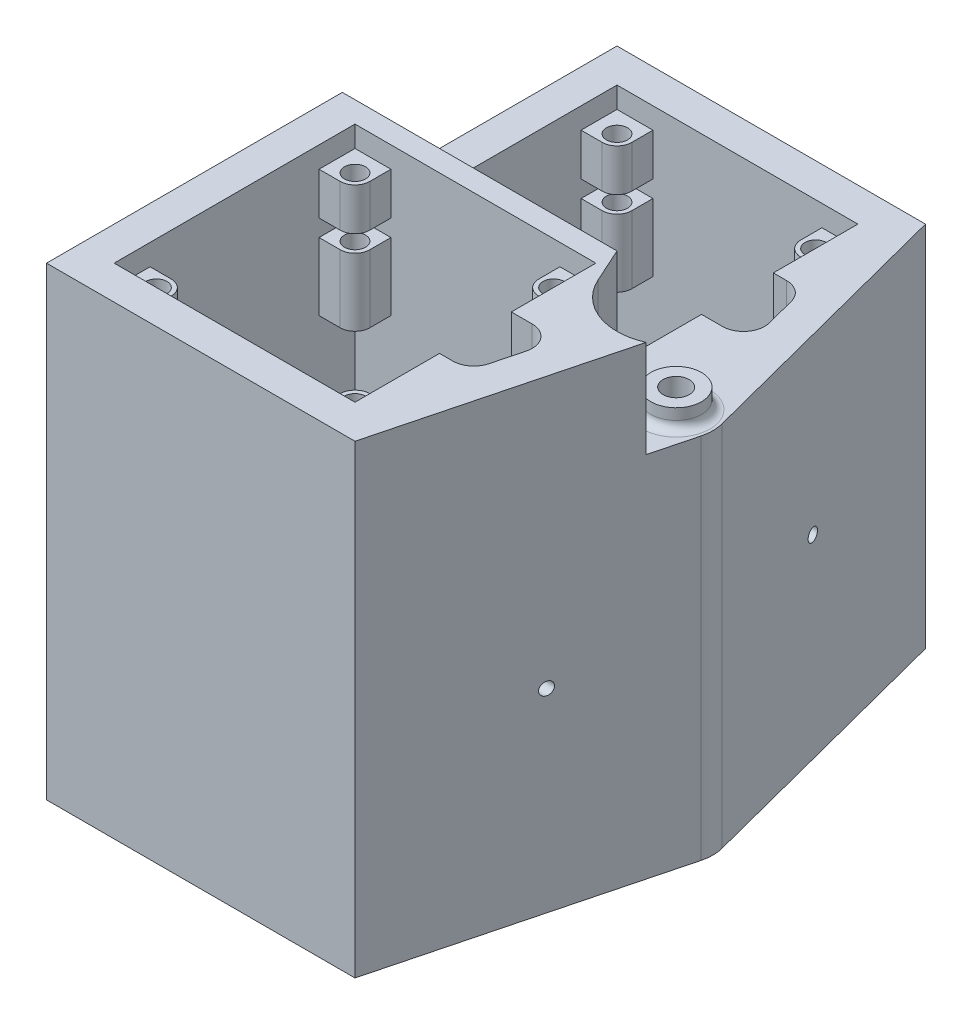
SolidWorks part; units mm, degrees
ref_plane "Alzado" through (0, 0, 0) normal (0, 0, 1) x (1, 0, 0)
ref_plane "Planta" through (0, 0, 0) normal (0, 1, 0) x (1, 0, 0)
ref_plane "Vista lateral" through (0, 0, 0) normal (1, 0, 0) x (0, 0, -1)
sketch "Croquis1" plane through (0, 0, 0) normal (0, 1, 0) x (1, 0, 0)
  line L0 (-55, 0) -> (55, 0) construction
  line L1 (-158, 67.5) -> (0, 67.5)
  line L2 (-158, 67.5) -> (-158, -67.5)
  line L3 (-158, -67.5) -> (0, -67.5)
  line L5 (-158, 67.5) -> (0, -67.5) construction
  line L6 (-158, -67.5) -> (0, 67.5) construction
  line L8 (-58.5, 0) -> (-48.5, 0) construction
  line L9 (-58.5, 0) -> (-48.5, 0) construction
  line L10 (-150, 59.5) -> (-93, 59.5) construction
  line L11 (-150, 59.5) -> (-150, 2.5) construction
  line L12 (-150, 2.5) -> (-93, 2.5) construction
  line L13 (-93, 59.5) -> (-93, 2.5) construction
  arc A0 (0, -67.5) -> (0, 67.5) centre (0, 0) ccw
  circle A1 centre (0, 0) radius 48.5 construction
  circle A2 centre (-71, 0) radius 12.5 construction
  point P4 (-79, 0)
  dimension "D1" = 135
  dimension "D2" = 97
  dimension "D3" = 25
  dimension "D4" = 10
  dimension "D5" = 8
  dimension "D6" = 57
  dimension "D7" = 8
  dimension "D8" = 158
extrude "Saliente-Extruir1" add sketch "Croquis1" along normal blind 110
sketch "Croquis2" plane through (0, 110, 0) normal (0, 1, 0) x (1, 0, 0)
  line L0 (-158, 67.5) -> (-158, -67.5) construction
  line L1 (-140, 59.5) -> (-103, 59.5)
  line L2 (-150, 49.5) -> (-150, 12.5)
  line L3 (-150, 12.5) -> (-140, 12.5)
  line L4 (-93, 49.5) -> (-93, 12.5)
  line L5 (0, 67.5) -> (-158, 67.5) construction
  line L6 (-150, 49.5) -> (-140, 49.5)
  line L7 (-140, 49.5) -> (-140, 59.5)
  line L8 (-121.5, 59.5) -> (-121.5, 2.5) construction
  line L9 (-150, 31) -> (-93, 31) construction
  line L10 (-103, 49.5) -> (-103, 59.5)
  line L11 (-93, 49.5) -> (-103, 49.5)
  line L12 (-93, 12.5) -> (-103, 12.5)
  line L13 (-103, 12.5) -> (-103, 2.5)
  line L14 (-140, 12.5) -> (-140, 2.5)
  line L16 (-140, 2.5) -> (-103, 2.5)
  point P13 (-121.5, 31)
  dimension "D1" = 8
  dimension "D2" = 8
  dimension "D3" = 37
  dimension "D4" = 37
  dimension "D5" = 57
extrude "Cortar-Extruir1" cut sketch "Croquis2" against normal blind 102
fillet "Redondeo1" [suppressed] radius 2
fillet "Redondeo2" radius 5 4 edges at (-103, 59, -12.5) (-140, 59, -12.5) (-103, 59, -49.5) (-140, 59, -49.5)
sketch "Croquis3" plane through (0, 110, 0) normal (0, 1, 0) x (1, 0, 0)
  line L0 (-150, 49.5) -> (-150, 12.5) construction
  line L1 (-150, 2.5) -> (-93, 2.5)
  line L2 (-150, 2.5) -> (-150, 59.5)
  line L3 (-150, 59.5) -> (-93, 59.5)
  line L4 (-93, 2.5) -> (-93, 59.5)
  line L5 (-140, 2.5) -> (-103, 2.5) construction
  line L6 (-103, 59.5) -> (-140, 59.5) construction
  line L7 (-93, 12.5) -> (-93, 49.5) construction
extrude "Cortar-Extruir2" cut sketch "Croquis3" against normal blind 5
sketch "Croquis4" plane through (0, 110, 0) normal (0, 1, 0) x (1, 0, 0)
  circle A0 centre (0, 0) radius 6
  dimension "D1" = 12
extrude "Cortar-Extruir3" cut sketch "Croquis4" against normal blind 100
sketch "Croquis5" plane through (0, 110, 0) normal (0, 1, 0) x (1, 0, 0)
  line L0 (-60.5, 0) -> (60.5, 0) construction
  line L1 (-89, -1000) -> (-89, 49000) construction
  line L2 (-93, 12.5) -> (-93, 49.5) construction
  circle A1 centre (-76.5, 0) radius 12.5 construction
  circle A2 centre (-76.5, 0) radius 3.1
  circle A3 centre (0, 0) radius 62 construction
  dimension "D1" = 124
  dimension "D2" = 25
  dimension "D4" = 6.2
  dimension "D3" = 4
extrude "Cortar-Extruir4" cut sketch "Croquis5" against normal blind 100
sketch "Croquis6" plane through (0, 110, 0) normal (0, 1, 0) x (1, 0, 0)
  line L0 (-68.1506, 2.5096) -> (-85, 67.5)
  line L1 (0, 67.5) -> (-158, 67.5) construction
  line L2 (-85, 67.5) -> (0, 67.5)
  line L3 (-60.5, 0) -> (60.5, 0) construction
  line L4 (-85, -67.5) -> (0, -67.5)
  line L5 (-68.1506, -2.5096) -> (-85, -67.5)
  line L6 (-93, 2.5) -> (-93, 59.5) construction
  arc A0 (0, -67.5) -> (0, 67.5) centre (0, 0) ccw
  arc A1 (0, -67.5) -> (0, 67.5) centre (0, 0) ccw construction
  arc A2 (-68.1506, 2.5096) -> (-68.1506, -2.5096) centre (-77.8306, 0) cw
  point P20 (-67.5, 0)
  dimension "D2" = 10
  dimension "D1" = 8
extrude "Cortar-Extruir5" cut sketch "Croquis6" against normal blind 32
sketch "Croquis7" plane through (0, 110, 0) normal (0, 1, 0) x (1, 0, 0)
  line L0 (-70.8172, -12.7947) -> (-85, -67.5)
  line L1 (-68.1506, -2.5096) -> (-85, -67.5) construction
  line L2 (-85, -67.5) -> (-158, -67.5)
  line L3 (-93, 2.5) -> (-158, 2.5)
  line L4 (-158, 67.5) -> (-158, -67.5) construction
  line L5 (-158, 2.5) -> (-158, -67.5)
  line L6 (-140, 2.5) -> (-103, 2.5) construction
  line L7 (-93, 2.5) -> (-89.2537, -5.7744)
  arc A0 (-89.2537, -5.7744) -> (-70.8172, -12.7947) centre (-76.5, 0) ccw
  dimension "D1" = 28
extrude "Saliente-Extruir2" add sketch "Croquis7" along normal blind 23
sketch "Croquis8" plane through (0, 133, 0) normal (0, 1, 0) x (1, 0, 0)
  line L0 (-158, 0) -> (-93, 0) construction
  line L1 (-158, 2.5) -> (-158, -67.5) construction
  line L13 (-140, 59.5) -> (-140, 54.5)
  line L14 (-145, 49.5) -> (-150, 49.5)
  line L15 (-150, 49.5) -> (-150, 12.5)
  line L16 (-150, 12.5) -> (-145, 12.5)
  line L17 (-140, 7.5) -> (-140, 2.5)
  line L18 (-140, 2.5) -> (-103, 2.5)
  line L19 (-103, 2.5) -> (-103, 7.5)
  line L20 (-98, 12.5) -> (-93, 12.5)
  line L21 (-93, 12.5) -> (-93, 49.5)
  line L22 (-93, 49.5) -> (-98, 49.5)
  line L23 (-103, 54.5) -> (-103, 59.5)
  line L24 (-103, 59.5) -> (-140, 59.5)
  line L25 (-140, 59.5) -> (-140, 54.5) construction
  line L26 (-145, 49.5) -> (-150, 49.5) construction
  line L27 (-150, 49.5) -> (-150, 12.5) construction
  line L28 (-150, 12.5) -> (-145, 12.5) construction
  line L29 (-140, 7.5) -> (-140, 2.5) construction
  line L30 (-140, 2.5) -> (-103, 2.5) construction
  line L31 (-103, 2.5) -> (-103, 7.5) construction
  line L32 (-98, 12.5) -> (-93, 12.5) construction
  line L33 (-93, 12.5) -> (-93, 49.5) construction
  line L34 (-93, 49.5) -> (-98, 49.5) construction
  line L35 (-103, 54.5) -> (-103, 59.5) construction
  line L36 (-103, 59.5) -> (-140, 59.5) construction
  line L39 (-103, -59.5) -> (-140, -59.5)
  line L40 (-103, -54.5) -> (-103, -59.5)
  line L41 (-93, -49.5) -> (-98, -49.5)
  line L42 (-93, -12.5) -> (-93, -49.5)
  line L43 (-98, -12.5) -> (-93, -12.5)
  line L44 (-103, -2.5) -> (-103, -7.5)
  line L45 (-140, -2.5) -> (-103, -2.5)
  line L46 (-140, -7.5) -> (-140, -2.5)
  line L47 (-150, -12.5) -> (-145, -12.5)
  line L48 (-150, -49.5) -> (-150, -12.5)
  line L49 (-145, -49.5) -> (-150, -49.5)
  line L50 (-140, -59.5) -> (-140, -54.5)
  arc A12 (-145, 49.5) -> (-140, 54.5) centre (-145, 54.5) ccw
  arc A13 (-103, -54.5) -> (-98, -49.5) centre (-98, -54.5) cw
  arc A14 (-98, -12.5) -> (-103, -7.5) centre (-98, -7.5) cw
  arc A15 (-140, 7.5) -> (-145, 12.5) centre (-145, 7.5) ccw
  arc A16 (-140, -7.5) -> (-145, -12.5) centre (-145, -7.5) cw
  arc A17 (-145, -49.5) -> (-140, -54.5) centre (-145, -54.5) cw
  arc A18 (-98, 12.5) -> (-103, 7.5) centre (-98, 7.5) ccw
  arc A21 (-103, 54.5) -> (-98, 49.5) centre (-98, 54.5) ccw
  arc A24 (-145, 49.5) -> (-140, 54.5) centre (-145, 54.5) ccw construction
  arc A27 (-140, 7.5) -> (-145, 12.5) centre (-145, 7.5) ccw construction
  arc A30 (-98, 12.5) -> (-103, 7.5) centre (-98, 7.5) ccw construction
  arc A33 (-103, 54.5) -> (-98, 49.5) centre (-98, 54.5) ccw construction
  dimension "D1" = 0
extrude "Cortar-Extruir6" cut sketch "Croquis8" against normal blind 102
sketch "Croquis10" plane through (0, 133, 0) normal (0, 1, 0) x (1, 0, 0)
  line L8 (-150, -12.5) -> (-150, -49.5) construction
  line L9 (-150, -59.5) -> (-93, -59.5)
  line L10 (-150, -59.5) -> (-150, -2.5)
  line L11 (-150, -2.5) -> (-93, -2.5)
  line L12 (-93, -59.5) -> (-93, -2.5)
  line L13 (-150, -59.5) -> (-93, -2.5) construction
  line L14 (-150, -2.5) -> (-93, -59.5) construction
  line L15 (-103, -2.5) -> (-140, -2.5) construction
  line L16 (-93, -49.5) -> (-93, -12.5) construction
  line L17 (-140, -59.5) -> (-103, -59.5) construction
  point P0 (-121.5, -31)
extrude "Cortar-Extruir7" cut sketch "Croquis10" against normal blind 5
sketch "Croquis11" plane through (0, 78, 0) normal (0, 1, 0) x (1, 0, 0)
  line L1 (0, 0) -> (-63, 0) construction
  circle A0 centre (0, 0) radius 63
  circle A1 centre (0, 0) radius 45 construction
  dimension "D1" = 126
  dimension "D2" = 90
extrude "Cortar-Extruir8" cut sketch "Croquis11" against normal blind 3 and the other way through all
sketch "Croquis12" plane through (0, 78, 0) normal (0, 1, 0) x (1, 0, 0)
  circle A0 centre (0, 0) radius 55
  dimension "D1" = 110
extrude "Cortar-Extruir9" cut sketch "Croquis12" against normal blind 13
sketch "Croquis13" plane through (0, 65, 0) normal (0, 1, 0) x (1, 0, 0)
  circle A0 centre (0, 0) radius 37.5 construction
  circle A1 centre (-37.5, 0) radius 1.75
  dimension "D1" = 75
  dimension "D2" = 3.5
extrude "Cortar-Extruir10" cut sketch "Croquis13" against normal blind 14
sketch "Croquis14" plane through (0, 65, 0) normal (0, 1, 0) x (1, 0, 0)
  circle A0 centre (-37.5, 0) radius 2.25
  dimension "D1" = 4.5
extrude "Cortar-Extruir11" cut sketch "Croquis14" against normal blind 5
pattern_circular "MatrizC1" count 6 over 360 about axis through (0, 0, 0) along (0, 1, 0) of "Cortar-Extruir11", "Cortar-Extruir10"
sketch "Croquis16" plane through (0, 110, 0) normal (0, 1, 0) x (1, 0, 0)
  circle A0 centre (-98, 7.5) radius 2.75 construction
  circle A1 centre (-145, 7.5) radius 2.75 construction
  circle A2 centre (-98, 54.5) radius 2.75 construction
  circle A3 centre (-145, 54.5) radius 2.75 construction
  circle A4 centre (-98, 7.5) radius 2.75 construction
  circle A5 centre (-145, 7.5) radius 2.75 construction
  circle A6 centre (-98, 54.5) radius 2.75 construction
  circle A7 centre (-145, 54.5) radius 2.75 construction
  circle A8 centre (-145, 54.5) radius 2.5
  circle A9 centre (-98, 54.5) radius 2.5
  circle A10 centre (-145, 7.5) radius 2.5
  circle A11 centre (-98, 7.5) radius 2.5
  dimension "D1" = 5
sketch "Croquis17" plane through (0, 133, 0) normal (0, 1, 0) x (1, 0, 0)
  circle A0 centre (-145, -54.5) radius 2.75 construction
  circle A1 centre (-98, -54.5) radius 2.75 construction
  circle A2 centre (-98, -7.5) radius 2.75 construction
  circle A3 centre (-145, -7.5) radius 2.75 construction
  circle A4 centre (-145, -54.5) radius 2.75 construction
  circle A5 centre (-98, -54.5) radius 2.75 construction
  circle A6 centre (-98, -7.5) radius 2.75 construction
  circle A7 centre (-145, -7.5) radius 2.75 construction
  circle A8 centre (-145, -7.5) radius 2.5
  circle A9 centre (-98, -7.5) radius 2.5
  circle A10 centre (-145, -54.5) radius 2.5
  circle A11 centre (-98, -54.5) radius 2.5
  dimension "D1" = 5
ref_plane "Plano1" through (0, 39, 0) normal (0, -1, 0) x (-1, 0, 0)
extrude "Cortar-Extruir12" cut sketch "Croquis17" against normal blind 30
sketch "Croquis18" plane through (0, 128, 0) normal (0, 1, 0) x (1, 0, 0)
  circle A4 centre (-145, -7.5) radius 2.75
  circle A5 centre (-98, -7.5) radius 2.75
  circle A6 centre (-145, -54.5) radius 2.75
  circle A7 centre (-98, -54.5) radius 2.75
  dimension "D1" = 5.5
extrude "Cortar-Extruir13" [suppressed] cut sketch "Croquis18" against normal blind 6.6
extrude "Cortar-Extruir14" cut sketch "Croquis16" against normal blind 30
sketch "Croquis19" plane through (0, 105, 0) normal (0, 1, 0) x (1, 0, 0)
  circle A4 centre (-145, 54.5) radius 2.75
  circle A5 centre (-98, 54.5) radius 2.75
  circle A6 centre (-145, 7.5) radius 2.75
  circle A7 centre (-98, 7.5) radius 2.75
  dimension "D1" = 5.5
extrude "Cortar-InsertosMotor1" [suppressed] cut sketch "Croquis19" against normal blind 6.6
sketch "Croquis20" plane through (0, 0, 0) normal (0, -1, 0) x (1, 0, 0)
  line L0 (0, -67.5) -> (-158, -67.5) construction
  line L1 (-158, 67.5) -> (0, 67.5) construction
  line L2 (0, -67.5) -> (-158, -67.5)
  line L3 (-158, 67.5) -> (0, 67.5)
  arc A0 (0, -67.5) -> (0, 67.5) centre (0, 0) ccw construction
  arc A1 (0, -67.5) -> (0, 67.5) centre (0, 0) ccw
sketch "Croquis21" plane through (-158, 0, 0) normal (1, 0, 0) x (0, 0, -1)
  line L0 (-67.5, 0) -> (67.5, 0) construction
  line L1 (-67.5, 0) -> (-81.5, 0)
  line L2 (-67.5, 0) -> (-67.5, 39)
  line L4 (-81.5, 0) -> (-81.5, 37.2595)
  line L5 (-55, 39) -> (55, 39) construction
  line L6 (-80.9119, 40.6381) -> (-67.5, 78)
  line L7 (-67.5, 78) -> (-67.5, 39)
  arc A0 (-80.9119, 40.6381) -> (-81.5, 37.2595) centre (-71.5, 37.2595) ccw
  point P12 (-81.5, 39)
  dimension "D2" = 10
  dimension "D1" = 14
sweep "Barrer1" add profiles "Croquis21" path "Croquis20"
sketch "Croquis22" plane through (0, 39, 0) normal (0, -1, 0) x (-1, 0, 0)
  line L0 (0, -74.206) -> (158, -74.206) construction
  line L1 (158, -67.5) -> (158, -80.9119) construction
  line L2 (0, 74.206) -> (158, 74.206) construction
  line L3 (158, 67.5) -> (158, 80.9119) construction
  line L4 (0, 0) -> (158, 0) construction
  line L5 (158, 2.5) -> (158, -67.5) construction
  line L6 (0, 0) -> (-52.4715, 52.4715) construction
  arc A0 (0, 74.206) -> (0, -74.206) centre (0, 0) ccw construction
  circle A1 centre (118.5, 74.206) radius 3
  circle A2 centre (39.5, 74.206) radius 3
  circle A3 centre (-52.4715, 52.4715) radius 3
  circle A4 centre (118.5, -74.206) radius 3
  circle A5 centre (39.5, -74.206) radius 3
  circle A6 centre (-52.4715, -52.4715) radius 3
  dimension "D1" = 79
  dimension "D2" = 39.5
  dimension "D3" = 6
  dimension "D4" = 45
extrude "Cortar-Extruir16" cut sketch "Croquis22" against normal through all both and the other way through all
sketch "Croquis23" plane through (0, 0, 0) normal (0, 1, 0) x (1, 0, 0)
  line L0 (0, 0) -> (-158, 0) construction
  line L1 (-158, 2.5) -> (-158, -67.5) construction
  circle A0 centre (-118.5, 74.206) radius 5
  circle A1 centre (-39.5, 74.206) radius 5
  circle A2 centre (52.4715, 52.4715) radius 5
  circle A3 centre (52.4715, 52.4715) radius 3 construction
  circle A4 centre (52.4715, -52.4715) radius 5
  circle A5 centre (-39.5, -74.206) radius 5
  circle A6 centre (-118.5, -74.206) radius 5
  dimension "D1" = 10
extrude "Cortar-Extruir17" cut sketch "Croquis23" along normal through all from offset 30
sketch "Croquis24" plane through (0, 78, 0) normal (0, 1, 0) x (1, 0, 0)
  line L0 (0, 67.5) -> (0, 96.2987)
  line L1 (0, -60.5) -> (0, 60.5) construction
  line L2 (0, -67.5) -> (0, -96.2987)
  arc A0 (0, 67.5) -> (0, -67.5) centre (0, 0) ccw
  arc A1 (0, -96.2987) -> (0, 96.2987) centre (0, 0) ccw
  arc A2 (0, -67.5) -> (0, 67.5) centre (0, 0) ccw construction
extrude "Cortar-Extruir18" cut sketch "Croquis24" against normal through all
sketch "Croquis25" plane through (-158, 0, 0) normal (-1, 0, 0) x (0, 0, 1)
  line L0 (-2.5, 133) -> (-2.5, 110) construction
  line L1 (12.5, 8) -> (52.5, 8)
  line L2 (12.5, 8) -> (12.5, 23)
  line L3 (12.5, 23) -> (52.5, 23)
  line L4 (52.5, 8) -> (52.5, 23)
  line L5 (12.5, 8) -> (52.5, 23) construction
  line L6 (12.5, 23) -> (52.5, 8) construction
  line L7 (-81.5, 0) -> (81.5, 0) construction
  line L9 (67.5, 0) -> (67.5, 78) construction
  line L10 (12.5, 31) -> (49.5, 31) construction
  point P0 (32.5, 15.5)
  dimension "D1" = 15
  dimension "D2" = 8
  dimension "D3" = 8
  dimension "D4" = 15
extrude "Cortar-Extruir19" cut sketch "Croquis25" against normal through all
ref_plane "Plano2" through (0, 42, 0) normal (0, 1, 0) x (1, 0, 0)
ref_plane "Plano4" through (0, 60, 0) normal (0, 1, 0) x (1, 0, 0)
sketch "Croquis26" plane through (0, 60, 0) normal (0, 1, 0) x (1, 0, 0)
  line L0 (-85, -67.5) -> (0, -67.5) construction
  line L1 (0, 67.5) -> (-85, 67.5) construction
  line L2 (-85, 67.5) -> (-68.1506, 2.5096) construction
  line L3 (-68.1506, -2.5096) -> (-70.8172, -12.7947) construction
  line L4 (-85, -67.5) -> (-70.8172, -12.7947) construction
  line L5 (-85, -67.5) -> (0, -67.5)
  line L6 (0, 67.5) -> (-85, 67.5)
  line L7 (-85, 67.5) -> (-68.1506, 2.5096)
  line L8 (-68.1506, -2.5096) -> (-70.8172, -12.7947)
  line L9 (-85, -67.5) -> (-70.8172, -12.7947)
  line L10 (0, 67.5) -> (0, -67.5)
  arc A0 (-68.1506, -2.5096) -> (-68.1506, 2.5096) centre (-77.8306, 0) ccw construction
  arc A1 (-68.1506, -2.5096) -> (-68.1506, 2.5096) centre (-77.8306, 0) ccw
extrude "Cortar-Extruir20" cut sketch "Croquis26" against normal through all
sketch "Croquis27" plane through (0, 133, 0) normal (0, 1, 0) x (1, 0, 0)
  line L1 (-93, -39.5) -> (-89.8742, -39.5)
  line L2 (-92.744, -65.4923) -> (-78.5611, -10.787)
  line L3 (-85.0343, -35.7548) -> (-83.2194, -28.7548)
  line L5 (-93, -22.5) -> (-88.0594, -22.5)
  line L8 (-93, -22.5) -> (-93, -39.5)
  line L9 (-158, 0) -> (-76.5, 0) construction
  line L10 (-158, 2.5) -> (-158, -67.5) construction
  line L11 (-93, 22.5) -> (-93, 39.5)
  line L12 (-93, 22.5) -> (-88.0594, 22.5)
  line L13 (-85.0343, 35.7548) -> (-83.2194, 28.7548)
  line L14 (-93, 39.5) -> (-89.8742, 39.5)
  line L15 (-150, -59.5) -> (-93, -59.5) construction
  line L16 (-93, -2.5) -> (-150, -2.5) construction
  line L17 (-93, -59.5) -> (-93, -2.5) construction
  arc A0 (-85.0343, -35.7548) -> (-89.8742, -39.5) centre (-89.8742, -34.5) cw
  arc A1 (-83.2194, -28.7548) -> (-88.0594, -22.5) centre (-88.0594, -27.5) ccw
  arc A2 (-83.2194, 28.7548) -> (-88.0594, 22.5) centre (-88.0594, 27.5) cw
  arc A3 (-85.0343, 35.7548) -> (-89.8742, 39.5) centre (-89.8742, 34.5) ccw
  dimension "D4" = 5
  dimension "D2" = 20
  dimension "D3" = 20
  dimension "D1" = 8
extrude "Cortar-Extruir21" cut sketch "Croquis27" against normal up to surface (125 mm away) up to face at (-121.5, 8, -31)
sketch "Croquis28" plane through (0, 8, 0) normal (0, 1, 0) x (1, 0, 0)
  line L0 (-83.2194, 28.7548) -> (-76.4151, 2.5096)
  line L1 (-83.2194, 28.7548) -> (-85.0343, 35.7548) construction
  line L2 (-83.2194, -28.7548) -> (-76.4151, -2.5096)
  line L3 (-85.0343, -35.7548) -> (-83.2194, -28.7548) construction
  line L4 (-93, -39.5) -> (-89.8742, -39.5) construction
  line L5 (-89.8742, 39.5) -> (-93, 39.5) construction
  line L6 (-93, -39.5) -> (-89.8742, -39.5)
  line L7 (-85.0343, -35.7548) -> (-83.2194, -28.7548)
  line L8 (-89.8742, 39.5) -> (-93, 39.5)
  line L9 (-83.2194, 28.7548) -> (-85.0343, 35.7548)
  line L10 (-93, 39.5) -> (-93, -39.5)
  arc A4 (-89.8742, -39.5) -> (-85.0343, -35.7548) centre (-89.8742, -34.5) ccw construction
  arc A5 (-85.0343, 35.7548) -> (-89.8742, 39.5) centre (-89.8742, 34.5) ccw construction
  arc A6 (-89.8742, -39.5) -> (-85.0343, -35.7548) centre (-89.8742, -34.5) ccw
  arc A7 (-85.0343, 35.7548) -> (-89.8742, 39.5) centre (-89.8742, 34.5) ccw
  arc A8 (-76.4151, -2.5096) -> (-76.4151, 2.5096) centre (-86.0951, 0) ccw
  dimension "D1" = 10
extrude "Cortar-Extruir22" cut sketch "Croquis28" along normal up to surface (15 mm away) up to face at (-88.3355, 23, 31.3582)
ref_plane "Plano3" through (0, 0, 0) normal (0, 0, -1) x (-1, 0, 0)
sketch "Croquis29" plane through (-158, 0, 0) normal (-1, 0, 0) x (0, 0, 1)
  line L0 (12.5, 8) -> (52.5, 8) construction
  line L1 (52.5, 8) -> (52.5, 23) construction
  line L2 (12.5, 23) -> (52.5, 23) construction
  line L3 (12.5, 8) -> (12.5, 23) construction
  line L4 (12.5, 8) -> (52.5, 8) construction
  line L5 (52.5, 8) -> (52.5, 23) construction
  line L6 (12.5, 23) -> (52.5, 23) construction
  line L7 (12.5, 8) -> (12.5, 23) construction
  line L8 (0, 133) -> (0, 0) construction
  line L9 (0, 35.75) -> (0, -35.75) construction
  line L10 (-2.5, 133) -> (67.5, 133) construction
  line L11 (-12.5, 8) -> (-12.5, 23)
  line L12 (-12.5, 23) -> (-52.5, 23)
  line L13 (-52.5, 8) -> (-52.5, 23)
  line L14 (-12.5, 8) -> (-52.5, 8)
extrude "Cortar-Extruir24" cut sketch "Croquis29" along normal up to surface (21.8889 mm away) from surface
sketch "Croquis30" plane through (0, 31, 0) normal (0, 1, 0) x (1, 0, 0)
  line L0 (-93, -12.5) -> (-158, -12.5) construction
  line L1 (-132, -52.5) -> (-111, -52.5)
  line L2 (-140, -44.5) -> (-140, -20.5)
  line L3 (-132, -12.5) -> (-111, -12.5)
  line L4 (-103, -44.5) -> (-103, -20.5)
  line L5 (-140, -52.5) -> (-103, -12.5) construction
  line L6 (-140, -12.5) -> (-103, -52.5) construction
  line L7 (-81.1111, -52.5) -> (-158, -52.5) construction
  line L10 (-140, -2.5) -> (-140, -7.5) construction
  line L11 (-103, -7.5) -> (-103, -2.5) construction
  arc A0 (-111, -12.5) -> (-103, -20.5) centre (-111, -20.5) cw
  arc A1 (-103, -44.5) -> (-111, -52.5) centre (-111, -44.5) cw
  arc A2 (-132, -52.5) -> (-140, -44.5) centre (-132, -44.5) cw
  arc A3 (-140, -20.5) -> (-132, -12.5) centre (-132, -20.5) cw
  point P0 (-121.5, -32.5)
  dimension "D1" = 8
extrude "Cortar-Extruir25" cut sketch "Croquis30" against normal up to next
sketch "Croquis31" plane through (-158, 0, 0) normal (-1, 0, 0) x (0, 0, 1)
  line L2 (60.5, 8) -> (60.5, 23)
  line L3 (60.5, 8) -> (60.5, 23)
  line L4 (4.5, 23) -> (60.5, 23)
  line L6 (4.5, 23) -> (4.5, 8)
  line L7 (4.5, 23) -> (4.5, 8)
  line L8 (4.5, 8) -> (60.5, 8)
  dimension "D1" = 8
  dimension "D2" = 8
extrude "Cortar-Extruir26" cut sketch "Croquis31" against normal blind 3
sketch "Croquis32" plane through (-155, 0, 0) normal (-1, 0, 0) x (0, 0, 1)
  line L0 (32.5, 23) -> (32.5, 8) construction
  line L1 (60.5, 23) -> (4.5, 23) construction
  line L2 (4.5, 8) -> (60.5, 8) construction
  line L3 (4.5, 15.5) -> (60.5, 15.5) construction
  line L4 (4.5, 23) -> (4.5, 8) construction
  line L5 (60.5, 8) -> (60.5, 23) construction
  line L6 (4.5, 23) -> (4.5, 8) construction
  circle A0 centre (8.5, 15.5) radius 1.5
  circle A1 centre (56.5, 15.5) radius 1.5
  dimension "D1" = 3
  dimension "D2" = 4
extrude "Cortar-Extruir27" cut sketch "Croquis32" against normal blind 10
sketch "Croquis33" plane through (0, 78, 0) normal (0, 1, 0) x (1, 0, 0)
  line L0 (-76.5, 0) -> (0, 0) construction
  line L1 (-55.1033, 0) -> (-72.6033, 67.5) construction
  line L2 (0, 67.5) -> (-85, 67.5) construction
  line L3 (-85, 67.5) -> (-68.1506, 2.5096) construction
  circle A0 centre (-70.0107, 57.5) radius 2.5
  circle A1 centre (-65.344, 39.5) radius 2.5
  circle A2 centre (-65.344, -39.5) radius 2.5
  circle A3 centre (-70.0107, -57.5) radius 2.5
  dimension "D2" = 10
  dimension "D3" = 5
  dimension "D4" = 18
  dimension "D1" = 12
extrude "Cortar-Extruir28" cut sketch "Croquis33" against normal through all
sketch "Croquis34" plane through (0, 78, 0) normal (0, 1, 0) x (1, 0, 0)
  circle A0 centre (-70.0107, 57.5) radius 4.25
  circle A1 centre (-65.344, 39.5) radius 4.25
  circle A2 centre (-65.344, -39.5) radius 4.25
  circle A3 centre (-70.0107, -57.5) radius 4.25
  dimension "D1" = 8.5
extrude "Cortar-Extruir29" cut sketch "Croquis34" against normal blind 5
sketch "Croquis35" plane through (0, 0, -81.5) normal (0, 0, -1) x (-1, 0, 0)
  line L0 (0, 60.5) -> (0, -60.5) construction
  line L1 (74.25, 0) -> (-74.25, 0) construction
  circle A0 centre (12, 28) radius 2.5
  circle A1 centre (12, 10) radius 2.5
  dimension "D1" = 12
  dimension "D2" = 10
  dimension "D3" = 5
  dimension "D4" = 18
extrude "Cortar-Extruir30" cut sketch "Croquis35" against normal up to next
sketch "Croquis36" plane through (0, 0, -81.5) normal (0, 0, -1) x (-1, 0, 0)
  circle A0 centre (12, 28) radius 4.25
  circle A1 centre (12, 10) radius 4.25
  dimension "D1" = 8.5
extrude "Cortar-Extruir31" cut sketch "Croquis36" against normal blind 5
mirror "Simetría2" about plane through (0, 0, 0) normal (0, 0, -1) of "Cortar-Extruir30", "Cortar-Extruir31"
sketch "Croquis37" plane through (-155, 0, 0) normal (-1, 0, 0) x (0, 0, 1)
  circle A0 centre (8.5, 15.5) radius 1.75
  circle A1 centre (56.5, 15.5) radius 1.75
  dimension "D1" = 3.5
extrude "Cortar-Extruir32" [suppressed] cut sketch "Croquis37" against normal blind 6
sketch "Croquis38" plane through (0, 110, 0) normal (0, 1, 0) x (1, 0, 0)
  circle A0 centre (-76.5, 0) radius 3.1 construction
  circle A1 centre (-76.5, 0) radius 3.1
  circle A2 centre (-76.5, 0) radius 6
  dimension "D1" = 12
extrude "Saliente-Extruir3" add sketch "Croquis38" along normal blind 4.6
fillet "Redondeo3" radius 2 1 edges at (-76.5, 110, 6)
sketch "Croquis39" plane through (-155, 0, 0) normal (-1, 0, 0) x (0, 0, 1)
  line L0 (32.5, 23) -> (32.5, 8) construction
  line L1 (4.6029, 15.5) -> (6.5514, 12.125)
  line L2 (6.5514, 12.125) -> (12.5, 12.125)
  line L5 (12.5, 18.875) -> (6.5514, 18.875)
  line L6 (6.5514, 18.875) -> (4.6029, 15.5)
  line L13 (60.5, 23) -> (4.5, 23) construction
  line L14 (4.5, 8) -> (60.5, 8) construction
  line L15 (12.5, 8) -> (12.5, 23) construction
  line L16 (12.5, 18.875) -> (12.5, 12.125)
  line L17 (11.4228, 13.8125) -> (13.0579, 16.6445) [skipped]
  line L18 (11.4228, 17.1875) -> (9.7878, 20.0195) [skipped]
  line L19 (52.5, 18.875) -> (52.5, 12.125)
  line L20 (58.4486, 18.875) -> (60.3971, 15.5)
  line L21 (52.5, 18.875) -> (58.4486, 18.875)
  line L22 (58.4486, 12.125) -> (52.5, 12.125)
  line L23 (60.3971, 15.5) -> (58.4486, 12.125)
  circle A0 centre (8.5, 15.5) radius 3.375 construction
  circle A1 centre (56.5, 15.5) radius 3.375 construction
  dimension "D1" = 6.75
extrude "Cortar-Extruir33" cut sketch "Croquis39" against normal blind 2.2 from offset 4 offset against normal yes
sketch "Croquis40" plane through (0, 105, 0) normal (0, 1, 0) x (1, 0, 0)
  line L2 (-150, 31) -> (-83.8015, 31) construction
  line L3 (-150, 59.5) -> (-150, 2.5) construction
  line L4 (-141.5, 59.5) -> (-141.5, 54.5)
  line L5 (-145, 51) -> (-150, 51)
  line L6 (-141.5, 59.5) -> (-141.5, 54.5)
  line L7 (-145, 51) -> (-150, 51)
  line L8 (-83.2194, 28.7548) -> (-85.0343, 35.7548) construction
  line L9 (-121.5, 59.5) -> (-121.5, 2.5) construction
  line L10 (-93, 59.5) -> (-150, 59.5) construction
  line L11 (-93, 2.5) -> (-158, 2.5) construction
  line L12 (-141.5, 2.5) -> (-141.5, 7.5)
  line L13 (-145, 11) -> (-150, 11)
  line L14 (-98, 11) -> (-93, 11)
  line L15 (-101.5, 2.5) -> (-101.5, 7.5)
  line L16 (-98, 51) -> (-93, 51)
  line L17 (-101.5, 59.5) -> (-101.5, 54.5)
  line L18 (-150, 51) -> (-150, 11)
  line L19 (-141.5, 2.5) -> (-101.5, 2.5)
  line L20 (-93, 11) -> (-93, 51)
  line L21 (-101.5, 59.5) -> (-141.5, 59.5)
  arc A1 (-145, 11) -> (-141.5, 7.5) centre (-145, 7.5) cw
  arc A2 (-145, 51) -> (-141.5, 54.5) centre (-145, 54.5) ccw
  arc A3 (-145, 51) -> (-141.5, 54.5) centre (-145, 54.5) ccw
  arc A4 (-98, 51) -> (-101.5, 54.5) centre (-98, 54.5) cw
  arc A5 (-98, 11) -> (-101.5, 7.5) centre (-98, 7.5) ccw
  dimension "D1" = 1.5
extrude "Cortar-Extruir34" cut sketch "Croquis40" against normal up to surface (97 mm away) up to face at (-116.5958, 8, -8.1005)
sketch "Croquis41" plane through (0, 105, 0) normal (0, 1, 0) x (1, 0, 0)
  line L0 (-150, 59.5) -> (-150, 2.5) construction
  line L1 (-93, 59.5) -> (-150, 59.5) construction
  line L2 (-150, 59.5) -> (-150, 2.5)
  line L3 (-93, 59.5) -> (-150, 59.5)
  line L4 (-150, 2.5) -> (-93, 2.5)
  line L5 (-93, 2.5) -> (-93, 59.5)
extrude "Cortar-Extruir35" cut sketch "Croquis41" against normal up to surface (67 mm away) from offset 30 up to face at (-116.5508, 8, -7.9892) offset against normal yes
sketch "Croquis42" plane through (0, 0, 0) normal (1, 0, 0) x (0, 0, -1)
  line L0 (-67.5, 69) -> (67.5, 69) construction
  line L1 (-67.5, 60) -> (-67.5, 78) construction
  line L2 (67.5, 60) -> (67.5, 78) construction
  line L3 (0, -35.75) -> (0, 35.75) construction
  circle A0 centre (31.5, 69) radius 1.5
  circle A1 centre (-31.5, 69) radius 1.5
  dimension "D1" = 3
  dimension "D2" = 36
extrude "Cortar-Extruir36" cut sketch "Croquis42" against normal up to surface (93 mm away)
sketch "Croquis43" plane through (-93, 0, 0) normal (-1, 0, 0) x (0, 0, 1)
  line L0 (0, 35.75) -> (0, -35.75) construction
  line L1 (-27.7472, 69) -> (-29.6236, 72.25)
  line L2 (-29.6236, 72.25) -> (-33.3764, 72.25)
  line L3 (-33.3764, 72.25) -> (-35.2528, 69)
  line L4 (-35.2528, 69) -> (-33.3764, 65.75)
  line L5 (-33.3764, 65.75) -> (-29.6236, 65.75)
  line L6 (-29.6236, 65.75) -> (-27.7472, 69)
  line L7 (29.6236, 65.75) -> (27.7472, 69)
  line L8 (33.3764, 65.75) -> (29.6236, 65.75)
  line L9 (35.2528, 69) -> (33.3764, 65.75)
  line L10 (33.3764, 72.25) -> (35.2528, 69)
  line L11 (29.6236, 72.25) -> (33.3764, 72.25)
  line L12 (27.7472, 69) -> (29.6236, 72.25)
  circle A0 centre (-31.5, 69) radius 3.25 construction
  circle A1 centre (31.5, 69) radius 3.25 construction
  dimension "D1" = 6.5
extrude "Cortar-Extruir37" cut sketch "Croquis43" against normal blind 12
sketch "Croquis44" plane through (0, 0, 0) normal (1, 0, 0) x (0, 0, -1)
  line L0 (0, -35.75) -> (0, 35.75) construction
  circle A0 centre (31.5, 69) radius 3
  circle A1 centre (-31.5, 69) radius 3
  dimension "D1" = 6
extrude "Cortar-Extruir38" cut sketch "Croquis44" against normal blind 65
sketch "Croquis45" plane through (0, 133, 0) normal (0, 1, 0) x (1, 0, 0)
  line L1 (-158, -67.5) -> (-85, -67.5) construction
  line L2 (-85, -67.5) -> (-70.8172, -12.7947) construction
  line L3 (-68.1506, -2.5096) -> (-70.8172, -12.7947) construction
  line L4 (-85, 67.5) -> (-68.1506, 2.5096) construction
  line L5 (-85, 67.5) -> (-158, 67.5) construction
  line L6 (-158, -67.5) -> (-85, -67.5)
  line L7 (-85, -67.5) -> (-70.8172, -12.7947)
  line L8 (-68.1506, -2.5096) -> (-70.8172, -12.7947)
  line L9 (-85, 67.5) -> (-68.1506, 2.5096)
  line L10 (-85, 67.5) -> (-158, 67.5)
  arc A0 (-68.1506, -2.5096) -> (-68.1506, 2.5096) centre (-77.8306, 0) ccw construction
  arc A1 (-68.1506, -2.5096) -> (-68.1506, 2.5096) centre (-77.8306, 0) ccw
  spline S0 degree 3 poles (-158, 67.5) (-225.197, 141.2958) (92.4747, 209.649) (97.3846, -188.542) (-239.8862, -136.857) (-158, -67.5) knots 0 0 0 0 0.321989 0.672562 1 1 1 1
extrude "Cortar-Extruir39" cut sketch "Croquis45" against normal through all
sketch "Croquis46" plane through (0, 0, 0) normal (0, -1, 0) x (1, 0, 0)
  line L0 (-158, -67.5) -> (-158, 67.5) construction
  line L1 (-158, -67.5) -> (-85, -67.5) construction
  line L2 (-85, -67.5) -> (-68.1506, -2.5096) construction
  line L3 (-68.1506, 2.5096) -> (-85, 67.5) construction
  line L4 (-85, 67.5) -> (-158, 67.5) construction
  line L5 (-158, -67.5) -> (-158, 67.5)
  line L6 (-158, -67.5) -> (-85, -67.5)
  line L7 (-85, -67.5) -> (-68.1506, -2.5096)
  line L8 (-68.1506, 2.5096) -> (-85, 67.5)
  line L9 (-85, 67.5) -> (-158, 67.5)
  arc A0 (-68.1506, -2.5096) -> (-68.1506, 2.5096) centre (-77.8306, 0) ccw construction
  arc A1 (-68.1506, -2.5096) -> (-68.1506, 2.5096) centre (-77.8306, 0) ccw
extrude "Cortar-Extruir40" cut sketch "Croquis46" against normal up to surface (23 mm away) up to face at (-148.3314, 23, 32.5)
sketch "Croquis47" plane through (0, 128, 0) normal (0, 1, 0) x (1, 0, 0)
  line L6 (-121.5, -2.5) -> (-121.5, -59.5) construction
  line L7 (-93, -2.5) -> (-150, -2.5) construction
  line L8 (-145, -11) -> (-150, -11)
  line L9 (-141.5, -2.5) -> (-141.5, -7.5)
  line L10 (-145, -11) -> (-150, -11)
  line L11 (-141.5, -2.5) -> (-141.5, -7.5)
  line L12 (-150, -59.5) -> (-93, -59.5) construction
  line L13 (-150, -31) -> (-83.8015, -31) construction
  line L14 (-150, -2.5) -> (-150, -59.5) construction
  line L15 (-85.0343, -35.7548) -> (-83.2194, -28.7548) construction
  line L16 (-141.5, -59.5) -> (-141.5, -54.5)
  line L17 (-145, -51) -> (-150, -51)
  line L18 (-98, -51) -> (-93, -51)
  line L19 (-101.5, -59.5) -> (-101.5, -54.5)
  line L20 (-101.5, -2.5) -> (-101.5, -7.5)
  line L21 (-98, -11) -> (-93, -11)
  line L22 (-141.5, -2.5) -> (-101.5, -2.5)
  line L23 (-93, -11) -> (-93, -51)
  line L24 (-101.5, -59.5) -> (-141.5, -59.5)
  line L25 (-150, -51) -> (-150, -11)
  arc A3 (-145, -51) -> (-141.5, -54.5) centre (-145, -54.5) cw
  arc A4 (-145, -11) -> (-141.5, -7.5) centre (-145, -7.5) ccw
  arc A5 (-145, -11) -> (-141.5, -7.5) centre (-145, -7.5) ccw
  arc A6 (-98, -11) -> (-101.5, -7.5) centre (-98, -7.5) cw
  arc A7 (-98, -51) -> (-101.5, -54.5) centre (-98, -54.5) ccw
  dimension "D1" = 1.5
extrude "Cortar-Extruir41" cut sketch "Croquis47" against normal up to surface (97 mm away) up to face at (-121.5, 31, 32.5)
sketch "Croquis48" plane through (0, 128, 0) normal (0, 1, 0) x (1, 0, 0)
  line L0 (-150, -59.5) -> (-93, -59.5) construction
  line L1 (-150, -2.5) -> (-150, -59.5) construction
  line L2 (-93, -2.5) -> (-150, -2.5) construction
  line L3 (-150, -59.5) -> (-93, -59.5)
  line L4 (-150, -2.5) -> (-150, -59.5)
  line L5 (-93, -2.5) -> (-150, -2.5)
  line L6 (-93, -2.5) -> (-93, -59.5)
extrude "Cortar-Extruir42" cut sketch "Croquis48" against normal up to surface (67 mm away) from offset 30 up to face at (-118.3333, 31, 31) offset against normal yes
sketch "Croquis49" plane through (0, 105, 0) normal (0, 1, 0) x (1, 0, 0)
  line L0 (-93, 59.5) -> (-150, 59.5) construction
  line L7 (-150, 59.5) -> (-150, 2.5) construction
  line L8 (-93, 59.5) -> (-150, 59.5)
  line L9 (-150, 59.5) -> (-150, 2.5)
  line L10 (-150, 2.5) -> (-93, 2.5)
  line L11 (-93, 2.5) -> (-93, 59.5)
extrude "Cortar-Extruir43" cut sketch "Croquis49" against normal blind 4 from offset 10 offset against normal yes
sketch "Croquis50" plane through (0, 128, 0) normal (0, 1, 0) x (1, 0, 0)
  line L0 (-150, -59.5) -> (-93, -59.5) construction
  line L1 (-93, -59.5) -> (-93, -39.5) construction
  line L2 (-93, -39.5) -> (-93, -22.5) construction
  line L3 (-93, -22.5) -> (-93, -2.5) construction
  line L4 (-93, -2.5) -> (-150, -2.5) construction
  line L5 (-150, -2.5) -> (-150, -59.5) construction
  line L6 (-150, -59.5) -> (-93, -59.5)
  line L7 (-93, -59.5) -> (-93, -39.5)
  line L8 (-93, -39.5) -> (-93, -22.5)
  line L9 (-93, -22.5) -> (-93, -2.5)
  line L10 (-93, -2.5) -> (-150, -2.5)
  line L11 (-150, -2.5) -> (-150, -59.5)
extrude "Cortar-Extruir44" cut sketch "Croquis50" against normal blind 4 from offset 10
